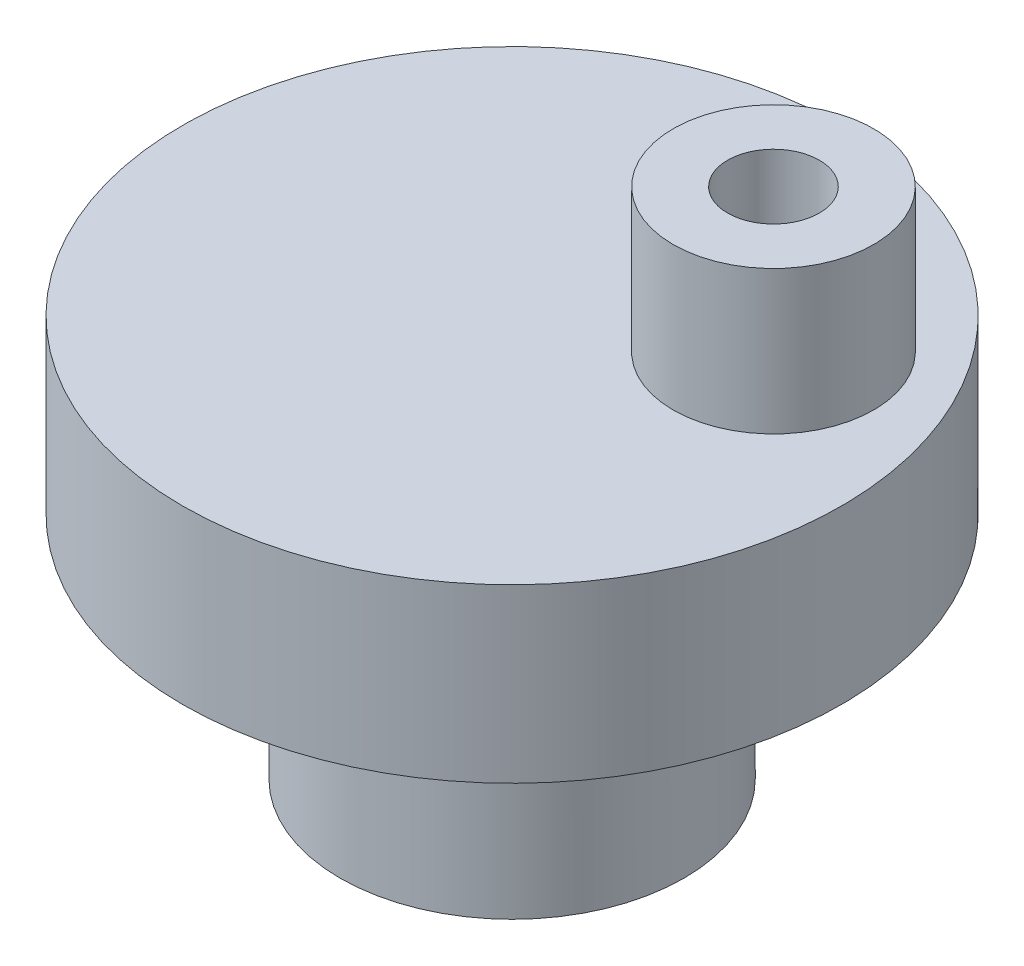
SolidWorks part; units mm, degrees
ref_plane "Front Plane" through (0, 0, 0) normal (0, 0, 1) x (1, 0, 0)
ref_plane "Top Plane" through (0, 0, 0) normal (0, 1, 0) x (1, 0, 0)
ref_plane "Right Plane" through (0, 0, 0) normal (1, 0, 0) x (0, 0, -1)
sketch "Sketch1" plane through (0, 0, 0) normal (0, 1, 0) x (1, 0, 0)
  circle A0 centre (0, 0) radius 5.75
  circle A1 centre (0, 0) radius 1.5
  dimension "D1" = 11.5
  dimension "D2" = 3
extrude "Boss-Extrude1" add sketch "Sketch1" along normal blind 3
sketch "Sketch2" plane through (0, 0, 0) normal (0, -1, 0) x (1, 0, 0)
  circle A0 centre (0, 0) radius 3
  circle A1 centre (0, 0) radius 1.5
  dimension "D1" = 6
  dimension "D2" = 3
extrude "Boss-Extrude2" add sketch "Sketch2" along normal blind 4
sketch "Sketch3" plane through (0, 3, 0) normal (0, 1, 0) x (1, 0, 0)
  line L0 (-0.8782, -1.216) -> (0.9268, -1.1795)
  arc A1 (-0.8782, -1.216) -> (0.9268, -1.1795) centre (0, 0) ccw
  circle A2 centre (0, 0) radius 1.5 construction
  dimension "D1" = 1.198
extrude "Boss-Extrude3" add sketch "Sketch3" against normal blind 7
sketch "Sketch4" plane through (0, 3, 0) normal (0, 1, 0) x (1, 0, 0)
  circle A0 centre (2.8306, 1.7295) radius 0.8
  circle A1 centre (2.8306, 1.7295) radius 1.75
  dimension "D2" = 3.5
extrude "Boss-Extrude4" add sketch "Sketch4" along normal blind 2.5
sketch "Sketch5" plane through (0, 3, 0) normal (0, 1, 0) x (1, 0, 0)
  circle A1 centre (0, 0) radius 5.75
  circle A2 centre (0, 0) radius 5.75
  dimension "D1" = 0
extrude "Boss-Extrude5" add sketch "Sketch5" against normal blind 0.8
